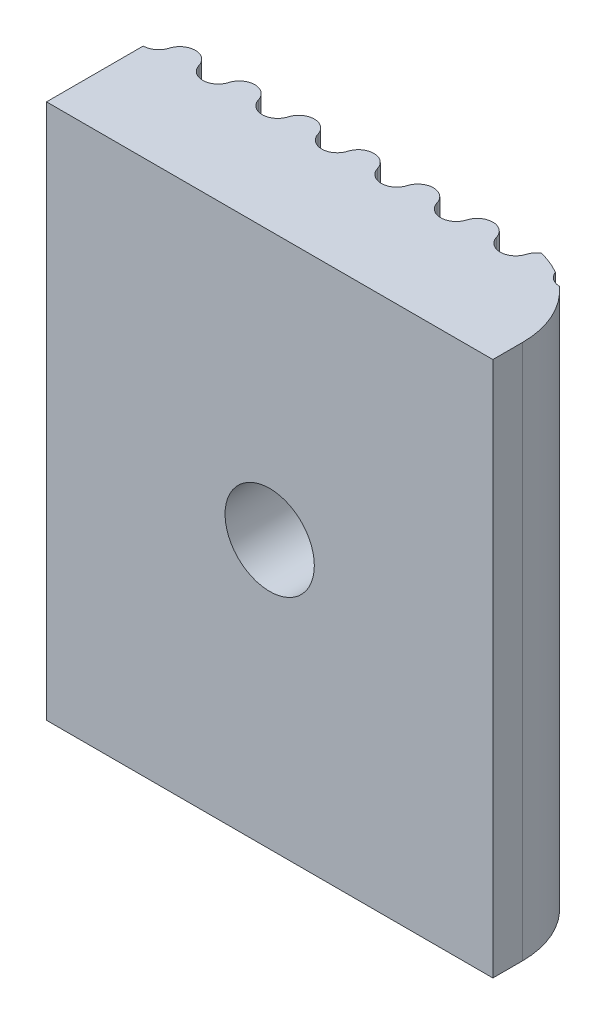
SolidWorks part; units mm, degrees
ref_plane "Front Plane" through (0, 0, 0) normal (0, 0, 1) x (1, 0, 0)
ref_plane "Top Plane" through (0, 0, 0) normal (0, 1, 0) x (1, 0, 0)
ref_plane "Right Plane" through (0, 0, 0) normal (1, 0, 0) x (0, 0, -1)
sketch "Sketch1" plane through (0, 0, 0) normal (0, 0, 1) x (1, 0, 0)
  line L0 (0, 18) -> (34.4, 18) construction
  line L1 (0, 0) -> (15, 0)
  line L2 (0, 0) -> (0, 18)
  line L3 (0, 18) -> (15, 18)
  line L4 (15, 0) -> (15, 18)
  line L5 (34.4, 18) -> (34.4, 0) construction
  line L6 (3.2858, 0) -> (-3.2858, 0) construction
  line L7 (34.4, 0) -> (0, 0) construction
  line L8 (7.5, 9) -> (26.9, 9) construction
  circle A0 centre (7.5, 9) radius 1.5
  point P11 (17.2, 9)
  point P13 (17.2, 18)
  point P14 (0, 0)
  point P15 (7.5, 18)
  point P16 (0, 9)
  dimension "D4" = 3
  dimension "D1" = 18
  dimension "D2" = 15
  dimension "D3" = 34.4
extrude "Boss-Extrude1" add sketch "Sketch1" along normal blind 4
fillet "Fillet1" radius 3 1 edges at (15, 9, 0)
sketch "Sketch2" plane through (0, 0, 0) normal (0, 1, 0) x (1, 0, 0)
  line L0 (-0.5, -0.375) -> (0.5, -0.375) construction
  line L1 (0, -0.75) -> (0, 0) construction
  line L2 (-1, 0) -> (1, 0)
  line L5 (-8.9682, 0) -> (8.9682, 0) construction
  line L6 (0, -3.3) -> (0, 3.3) construction
  arc A0 (-1, 0) -> (-0.5, -0.375) centre (-1, -0.5208) cw
  arc A1 (-0.5, -0.375) -> (0.5, -0.375) centre (0, -0.2292) ccw
  arc A2 (0.5, -0.375) -> (1, 0) centre (1, -0.5208) cw
  point P9 (0, -0.375)
  point P10 (0, -0.375)
  dimension "D1" = 0.75
  dimension "D2" = 2
  dimension "D3" = 1
extrude "Cut-Extrude2" cut sketch "Sketch2" along normal through all
pattern_linear "LPattern1" count 10 spacing 2 along (1, 0, 0) of "Cut-Extrude2"
